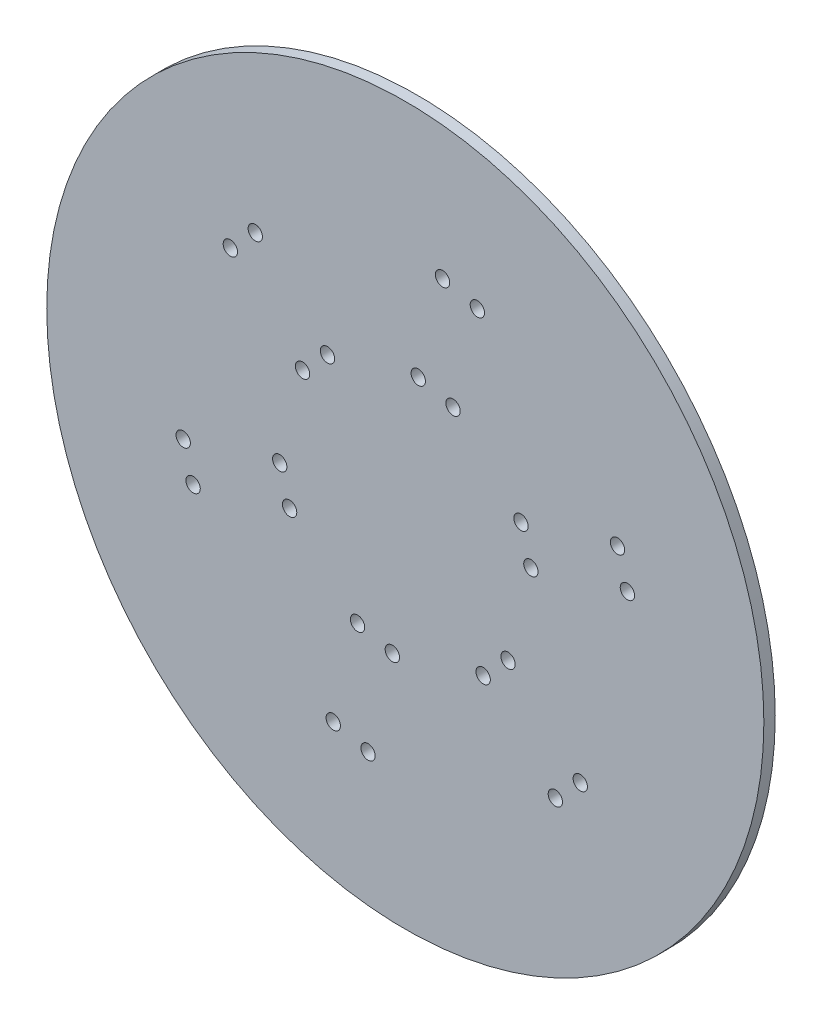
SolidWorks part; units mm, degrees
ref_plane "Front Plane" through (0, 0, 0) normal (0, 0, 1) x (1, 0, 0)
ref_plane "Top Plane" through (0, 0, 0) normal (0, 1, 0) x (1, 0, 0)
ref_plane "Right Plane" through (0, 0, 0) normal (1, 0, 0) x (0, 0, -1)
sketch "Sketch1" plane through (0, 0, 0) normal (0, 0, 1) x (1, 0, 0)
  circle A0 centre (0, 0) radius 100
  dimension "D1" = 200
extrude "Boss-Extrude1" add sketch "Sketch1" along normal blind 3.175
sketch "Sketch2" plane through (0, 0, 3.175) normal (0, 0, 1) x (1, 0, 0)
  line L0 (-71.9351, 69.4647) -> (71.9351, -69.4647) construction
  line L1 (-96.1257, -27.5653) -> (96.1257, 27.5653) construction
  line L2 (-24.1906, -97.03) -> (24.1906, 97.03) construction
  circle A0 centre (0, 0) radius 100 construction
  point P8 (0, 0)
  point P9 (0, 0)
  point P13 (0, 0)
  dimension "D1" = 60
  dimension "D2" = 60
sketch "Sketch6" plane through (0, 0, 3.175) normal (0, 0, 1) x (1, 0, 0)
  circle A0 centre (-10.3886, -62.3384) radius 2
  circle A1 centre (-20.0916, -59.9194) radius 2
  circle A2 centre (-3.6152, -35.17) radius 2
  circle A3 centre (-13.3182, -32.751) radius 2
  circle A4 centre (48.7924, -40.166) radius 2
  circle A5 centre (41.8459, -47.3595) radius 2
  circle A6 centre (21.7061, -27.8768) radius 2
  circle A7 centre (28.6505, -20.7159) radius 2
  circle A8 centre (61.9375, 12.5599) radius 2
  circle A9 centre (59.1809, 22.1724) radius 2
  circle A10 centre (32.2657, 14.4541) radius 2
  circle A11 centre (35.0223, 4.8416) radius 2
  circle A12 centre (20.0916, 59.9194) radius 2
  circle A13 centre (10.3886, 62.3384) radius 2
  circle A14 centre (3.6152, 35.17) radius 2
  circle A15 centre (13.3182, 32.751) radius 2
  circle A16 centre (-21.7041, 27.9094) radius 2
  circle A17 centre (-28.6505, 20.7159) radius 2
  circle A18 centre (-48.7924, 40.166) radius 2
  circle A19 centre (-41.8459, 47.3595) radius 2
  circle A20 centre (-32.2657, -14.4541) radius 2
  circle A21 centre (-35.0223, -4.8416) radius 2
  circle A22 centre (-59.1809, -22.1724) radius 2
  circle A23 centre (-61.9375, -12.5599) radius 2
  dimension "D1" = 4
extrude "Cut-Extrude1" cut sketch "Sketch6" against normal through all contours A8 | A9 | A11 | A10 | A15 | A14 | A12 | A13 | A16 | A17 | A19 | A18 | A21 | A20 | A23 | A22 | A2 | A3 | A0 | A1 | A7 | A4 | A5 | A6
